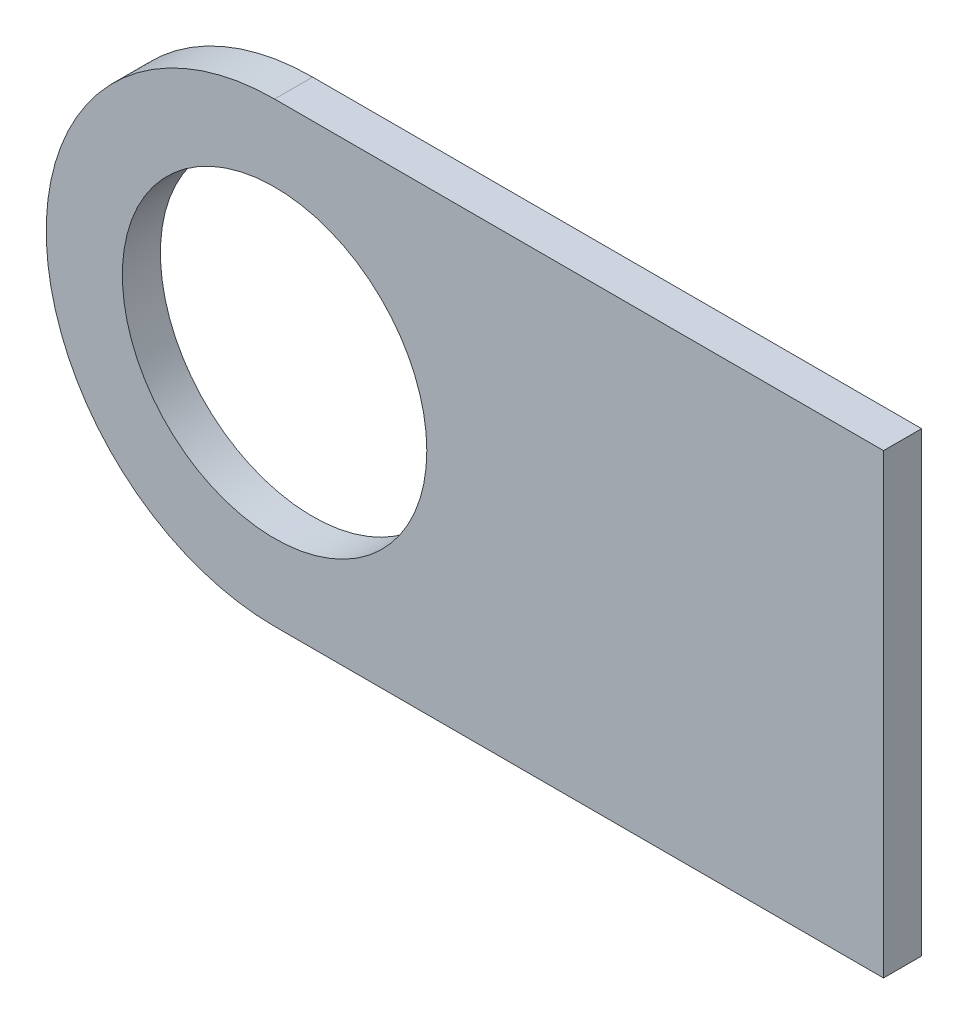
SolidWorks part; units mm, degrees
material "6061-T6 (SS)"
ref_plane "X-Y Datum" through (0, 0, 0) normal (0, 0, 1) x (1, 0, 0)
ref_plane "X-Z Datum" through (0, 0, 0) normal (0, 1, 0) x (1, 0, 0)
ref_plane "Y-Z Datum" through (0, 0, 0) normal (1, 0, 0) x (0, 0, -1)
sketch "Flat sketch" plane through (0, 0, 0) normal (0, 0, 1) x (1, 0, 0)
  line L0 (-12.7, 0) -> (72.263, 0) construction
  line L1 (0, 19.05) -> (0, -19.05) construction
  line L3 (0, 19.05) -> (50.8, 19.05)
  line L4 (0, 19.05) -> (0, -19.05)
  line L5 (0, -19.05) -> (50.8, -19.05)
  line L6 (50.8, 19.05) -> (50.8, -19.05)
  circle A0 centre (0, 0) radius 12.7
  circle A1 centre (0, 0) radius 19.05
  point P5 (12.7, 0)
  point P9 (19.05, 0)
  dimension "D1" = 25.4
  dimension "D2" = 38.1
  dimension "D3" = 50.8
extrude "Extrude face" add sketch "Flat sketch" along normal blind 3.175
equation "\"Torsion Bar O.D.\"= 1in"
equation "\"Lever I.D. Torsion O.D. Clearance\"= 0"
equation "\"Lever I.D.\"= \"Torsion Bar O.D.\" + \"Lever I.D. Torsion O.D. Clearance\""
equation "\"D1@Flat sketch\" = \"Lever I.D.\""
equation "\"Lever O.D.\"= 1.5"
equation "\"D2@Flat sketch\" = \"Lever O.D.\""
equation "\"Lever thickness\"= 1 / 8in"
equation "\"D1@Extrude face\" = \"Lever thickness\""
equation "\"Tab length\"= 2"
equation "\"D3@Flat sketch\"=\"Tab length\""
